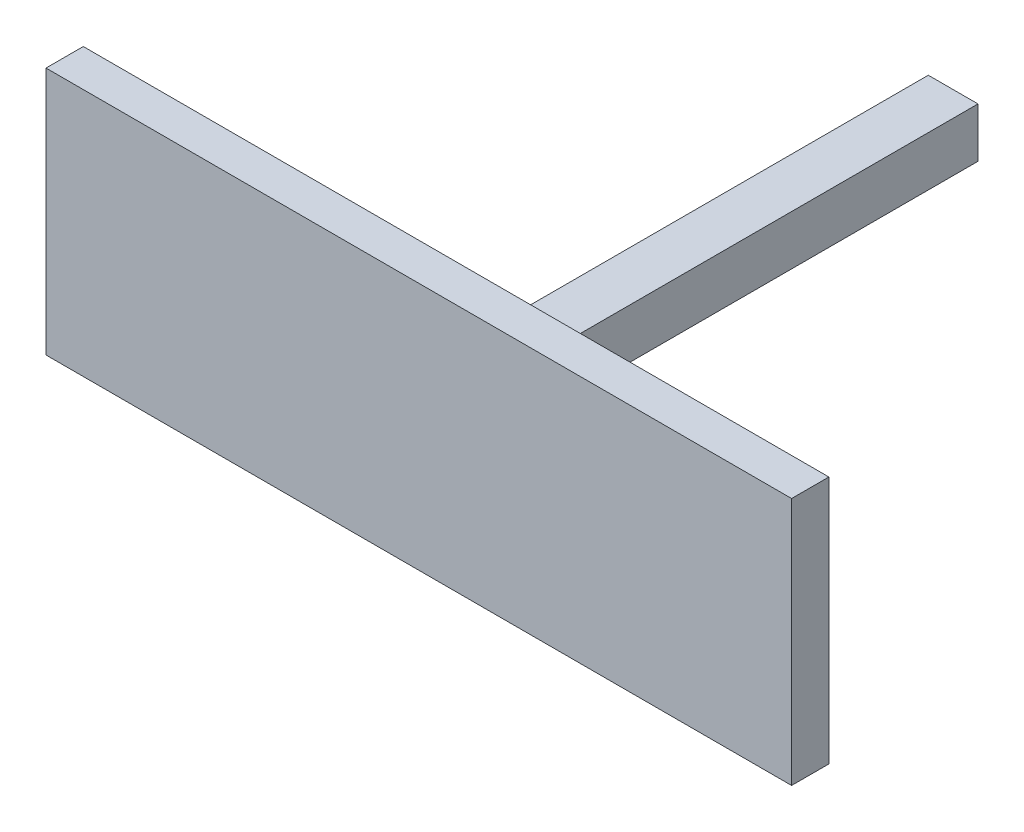
SolidWorks part; units mm, degrees
ref_plane "Plan de face" through (0, 0, 0) normal (0, 0, 1) x (1, 0, 0)
ref_plane "Plan de dessus" through (0, 0, 0) normal (0, 1, 0) x (1, 0, 0)
ref_plane "Plan de droite" through (0, 0, 0) normal (1, 0, 0) x (0, 0, -1)
sketch "Esquisse1" plane through (0, 0, 0) normal (0, 0, 1) x (1, 0, 0)
  line L1 (-30, -10) -> (30, -10)
  line L2 (-30, -10) -> (-30, 10)
  line L3 (-30, 10) -> (30, 10)
  line L4 (30, -10) -> (30, 10)
  line L5 (-30, -10) -> (30, 10) construction
  line L6 (-30, 10) -> (30, -10) construction
  point P0 (0, 0)
  dimension "D1" = 20
  dimension "D2" = 60
extrude "Boss.-Extru.1" add sketch "Esquisse1" along normal blind 3
sketch "Esquisse2" plane through (0, 0, 0) normal (0, 0, -1) x (-1, 0, 0)
  line L1 (-2, 2) -> (2, 2)
  line L2 (-2, 2) -> (-2, -2)
  line L3 (-2, -2) -> (2, -2)
  line L4 (2, 2) -> (2, -2)
  line L5 (-2, 2) -> (2, -2) construction
  line L6 (-2, -2) -> (2, 2) construction
  point P0 (0, 0)
  dimension "D1" = 4
  dimension "D2" = 4
extrude "Boss.-Extru.2" add sketch "Esquisse2" along normal blind 40
